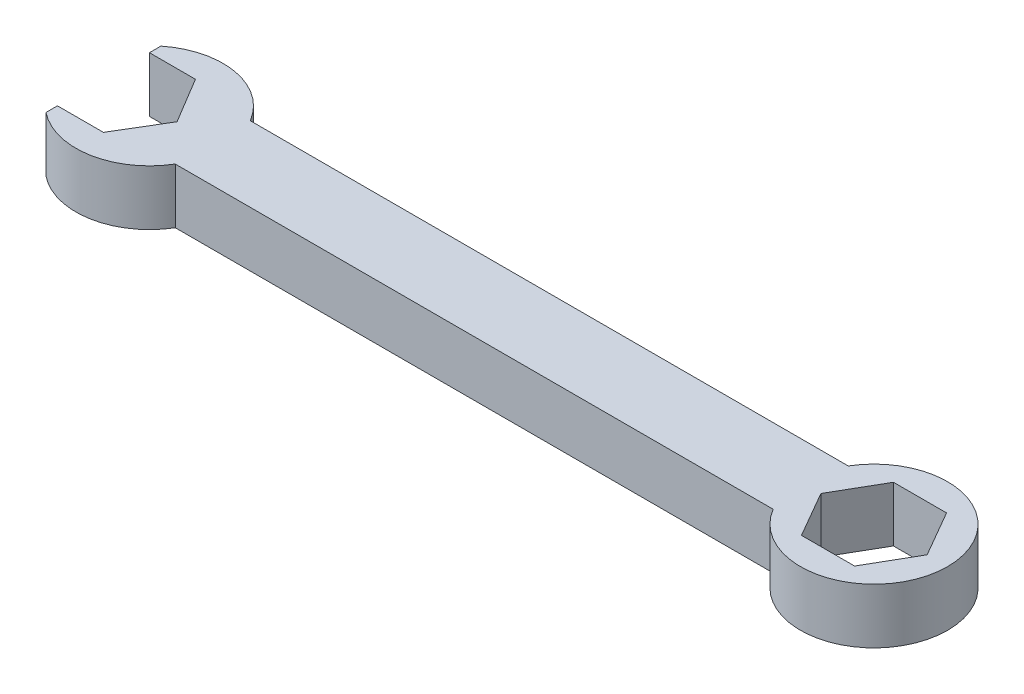
SolidWorks part; units mm, degrees
ref_plane "Front Plane" through (0, 0, 0) normal (0, 0, 1) x (1, 0, 0)
ref_plane "Top Plane" through (0, 0, 0) normal (0, 1, 0) x (1, 0, 0)
ref_plane "Right Plane" through (0, 0, 0) normal (1, 0, 0) x (0, 0, -1)
sketch "Sketch2" plane through (0, 0, 0) normal (0, 1, 0) x (1, 0, 0)
  line L0 (4.9313, 5.1783) -> (87.4813, 5.1783)
  line L1 (-2.6928, 0) -> (-28.7756, 0) construction
  line L2 (0, 0) -> (-3.81, 6.35)
  line L3 (-3.81, 6.35) -> (-10.16, 6.35)
  line L4 (-10.16, 6.35) -> (-10.16, 7.9311)
  line L5 (0, 0) -> (88.8903, 0)
  line L6 (103.555, 0) -> (99.8888, 6.35)
  line L7 (99.8888, 6.35) -> (92.5565, 6.35)
  line L8 (92.5565, 6.35) -> (88.8903, 0)
  line L12 (101.7219, -3.175) -> (103.555, 0) [skipped]
  line L13 (92.5565, -6.35) -> (99.8888, -6.35) [skipped]
  line L14 (88.8903, 0) -> (90.7234, -3.175) [skipped]
  line L15 (103.555, 0) -> (106.3827, 0)
  line L16 (103.555, 0) -> (99.8888, -6.35)
  line L17 (99.8888, -6.35) -> (92.5565, -6.35)
  line L18 (92.5565, -6.35) -> (88.8903, 0)
  line L19 (0, 0) -> (-3.81, -6.35)
  line L20 (-3.81, -6.35) -> (-10.16, -6.35)
  line L21 (-10.16, -6.35) -> (-10.16, -7.9311)
  line L22 (4.9313, -5.1783) -> (87.4813, -5.1783)
  arc A0 (4.9313, 5.1783) -> (-10.16, 7.9311) centre (-3.81, 0) ccw
  arc A1 (87.4813, -5.1783) -> (87.4813, 5.1783) centre (96.2227, 0) ccw
  arc A2 (102.5727, 0) -> (89.8727, 0) centre (96.2227, 0) ccw construction
  arc A3 (4.9313, -5.1783) -> (-10.16, -7.9311) centre (-3.81, 0) cw
  dimension "D1" = 20.32
  dimension "D7" = 20.32
  dimension "D2" = 82.55
  dimension "D3" = 6.35
  dimension "D4" = 10.16
  dimension "D5" = 6.35
  dimension "D6" = 3.81
extrude "Boss-Extrude1" add sketch "Sketch2" along normal blind 7.62 contours A3 L22 A1 L15 L16 L17 L18 L5 L19 L20 L21 | L15 A1 L0 A0 L4 L3 L2 L5 L8 L7 L6
